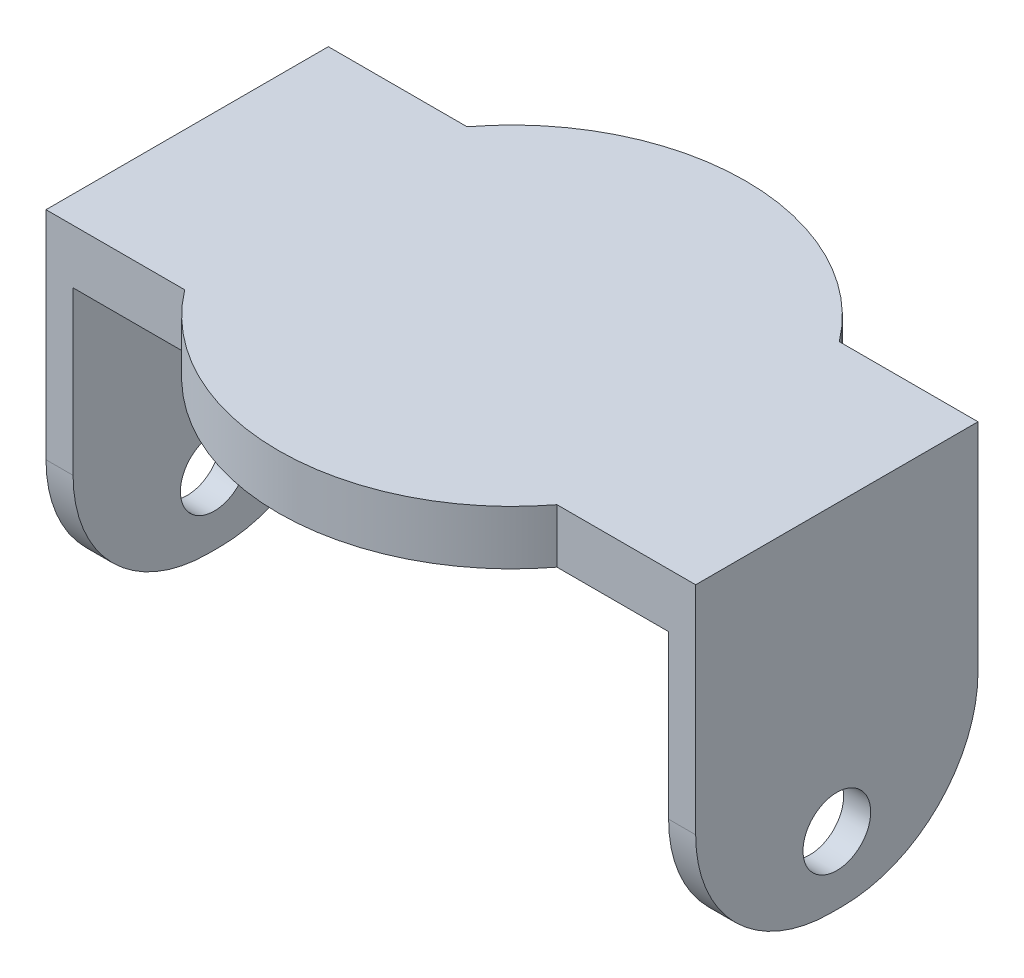
SolidWorks part; units mm, degrees
ref_plane "Alzado" through (0, 0, 0) normal (0, 0, 1) x (1, 0, 0)
ref_plane "Planta" through (0, 0, 0) normal (0, 1, 0) x (1, 0, 0)
ref_plane "Vista lateral" through (0, 0, 0) normal (1, 0, 0) x (0, 0, -1)
sketch "Croquis1" plane through (0, 0, 0) normal (0, 1, 0) x (1, 0, 0)
  line L1 (-24, 23) -> (24, 23)
  line L2 (-24, 23) -> (-24, -23)
  line L3 (-24, -23) -> (24, -23)
  line L4 (24, 23) -> (24, -23)
  line L5 (-24, 23) -> (24, -23) construction
  line L6 (-24, -23) -> (24, 23) construction
  point P0 (0, 0)
  dimension "D1" = 48
  dimension "D2" = 46
extrude "Saliente-Extruir1" add sketch "Croquis1" against normal blind 26
sketch "Croquis2" plane through (0, 0, 23) normal (0, 0, 1) x (1, 0, 0)
  line L0 (-24, -26) -> (24, -26) construction
  line L1 (-22, -26) -> (22, -26)
  line L2 (-22, -26) -> (-22, -4)
  line L3 (-22, -4) -> (22, -4)
  line L4 (22, -26) -> (22, -4)
  line L5 (-24, -26) -> (-24, 0) construction
  line L6 (24, -26) -> (24, 0) construction
  line L7 (-24, 0) -> (24, 0) construction
  dimension "D1" = 2
  dimension "D2" = 2
  dimension "D3" = 4
  dimension "D4" = 44
extrude "Cortar-Extruir1" cut sketch "Croquis2" against normal blind 46
sketch "Croquis3" plane through (24, 0, 0) normal (1, 0, 0) x (0, 0, -1)
  line L0 (-23, -26) -> (-23, 0) construction
  line L1 (-23, -4) -> (-10.43, -4)
  line L2 (-23, -4) -> (-23, -26)
  line L3 (-23, -26) -> (-10.43, -26)
  line L4 (-10.43, -4) -> (-10.43, -26)
  line L5 (-23, -26) -> (23, -26) construction
  line L6 (23, -26) -> (23, 0) construction
  line L7 (23, -4) -> (10.43, -4)
  line L8 (23, -4) -> (23, -26)
  line L9 (23, -26) -> (10.43, -26)
  line L10 (10.43, -4) -> (10.43, -26)
  line L11 (-23, 0) -> (23, 0) construction
  dimension "D1" = 20.86
  dimension "D2" = 12.57
  dimension "D3" = 4
  dimension "D4" = 4
extrude "Cortar-Extruir3" cut sketch "Croquis3" against normal through all
fillet "Redondeo3" radius 10 2 edges at (23, -26, -10.43) (23, -26, 10.43)
fillet "Redondeo4" radius 10 2 edges at (-23, -26, 10.43) (-23, -26, -10.43)
sketch "Croquis4" plane through (0, 0, 0) normal (0, 1, 0) x (1, 0, 0)
sketch "Croquis16" plane through (-24, 0, 0) normal (-1, 0, 0) x (0, 0, 1)
  line L1 (-23, 0) -> (-10.43, 0)
  line L2 (-23, 0) -> (-23, -4)
  line L3 (-23, -4) -> (-10.43, -4)
  line L4 (-10.43, 0) -> (-10.43, -4)
  line L5 (10.43, -4) -> (23, -4)
  line L6 (10.43, -4) -> (10.43, 0)
  line L7 (10.43, 0) -> (23, 0)
  line L8 (23, -4) -> (23, 0)
extrude "Cortar-Extruir19" cut sketch "Croquis16" against normal blind 10.25
sketch "Croquis21" plane through (24, 0, 0) normal (1, 0, 0) x (0, 0, -1)
  line L0 (-10.43, -4) -> (-23, -4) construction
  line L1 (-23, 0) -> (-10.43, 0)
  line L2 (-23, 0) -> (-23, -4)
  line L3 (-23, -4) -> (-10.43, -4)
  line L4 (-10.43, 0) -> (-10.43, -4)
  line L6 (10.43, -4) -> (23, -4)
  line L7 (10.43, -4) -> (10.43, 0)
  line L8 (10.43, 0) -> (23, 0)
  line L9 (23, -4) -> (23, 0)
extrude "Cortar-Extruir20" cut sketch "Croquis21" against normal blind 10.25
sketch "Croquis22" plane through (0, 0, 0) normal (0, 1, 0) x (1, 0, 0)
  line L0 (13.75, -10.43) -> (13.75, -23)
  line L1 (13.75, -23) -> (-13.75, -23)
  line L2 (-24, 0) -> (24, 0) construction
  line L3 (-13.75, -10.43) -> (-13.75, -23)
  line L4 (13.75, 10.43) -> (13.75, 23)
  line L5 (13.75, 23) -> (-13.75, 23)
  line L6 (-13.75, 10.43) -> (-13.75, 23)
  line L7 (24, -10.43) -> (24, 10.43) construction
  arc A1 (-13.75, -10.43) -> (13.75, -10.43) centre (0, 0) ccw
  arc A2 (-13.75, 10.43) -> (13.75, 10.43) centre (0, 0) cw
extrude "Cortar-Extruir21" cut sketch "Croquis22" against normal blind 10.25
sketch "Croquis23" plane through (-24, 0, 0) normal (-1, 0, 0) x (0, 0, 1)
  line L0 (0, -26) -> (0, 0) construction
  line L1 (-0.43, -26) -> (0.43, -26) construction
  line L2 (-10.43, 0) -> (10.43, 0) construction
  circle A0 centre (0, -21) radius 2.5
  dimension "D1" = 5
  dimension "D2" = 5
extrude "Cortar-Extruir22" cut sketch "Croquis23" against normal blind 53
